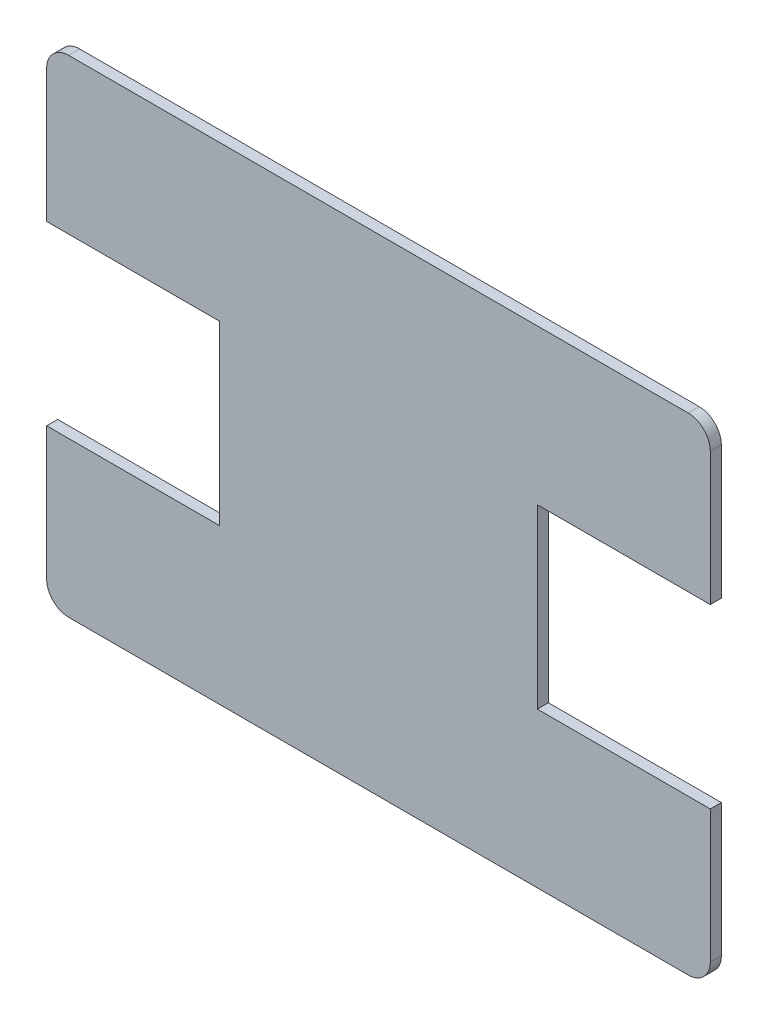
SolidWorks part; units mm, degrees
ref_plane "Front Plane" through (0, 0, 0) normal (0, 0, 1) x (1, 0, 0)
ref_plane "Top Plane" through (0, 0, 0) normal (0, 1, 0) x (1, 0, 0)
ref_plane "Right Plane" through (0, 0, 0) normal (1, 0, 0) x (0, 0, -1)
sketch "Sketch1" plane through (0, 0, 0) normal (0, 0, 1) x (1, 0, 0)
  line L0 (-150, 40) -> (-71.83, 40)
  line L1 (-140, 110) -> (140, 110)
  line L2 (-150, 100) -> (-150, 40)
  line L3 (-140, -110) -> (140, -110)
  line L4 (150, 100) -> (150, 40)
  line L5 (-71.83, 40) -> (-71.83, -40)
  line L6 (-71.83, -40) -> (-150, -40)
  line L7 (-150, 110) -> (150, -110) construction
  line L8 (0, 110) -> (0, -110) construction
  line L9 (150, 40) -> (71.83, 40)
  line L10 (71.83, 40) -> (71.83, -40)
  line L11 (71.83, -40) -> (150, -40)
  line L12 (-150, -40) -> (-150, -100)
  line L13 (150, -40) -> (150, -100)
  arc A0 (-150, -100) -> (-140, -110) centre (-140, -100) ccw
  arc A1 (140, -110) -> (150, -100) centre (140, -100) ccw
  arc A2 (140, 110) -> (150, 100) centre (140, 100) cw
  arc A3 (-140, 110) -> (-150, 100) centre (-140, 100) ccw
  point P6 (-71.83, 0)
  point P9 (0, 0)
  point P19 (-150, -110)
  point P25 (150, 110)
  dimension "D6" = 10
  dimension "D1" = 300
  dimension "D2" = 220
  dimension "D3" = 78.17
  dimension "D4" = 80
  dimension "D5" = 110
extrude "Boss-Extrude1" add sketch "Sketch1" along normal blind 5
sketch "Sketch2" plane through (0, 0, 5) normal (0, 0, 1) x (1, 0, 0)
  line L0 (-150, 40) -> (-71.83, 40) construction
  line L1 (-71.83, 40) -> (-71.83, -40) construction
  line L2 (0, 110) -> (0, -110) construction
  line L3 (140, 110) -> (-140, 110) construction
  line L4 (-140, -110) -> (140, -110) construction
  circle A0 centre (-56.13, 16) radius 2
  circle A1 centre (-37.13, 16) radius 2
  circle A2 centre (-18.13, 16) radius 2
  circle A3 centre (-56.13, -16) radius 2
  circle A4 centre (-37.13, -16) radius 2
  circle A5 centre (-18.13, -16) radius 2
  circle A6 centre (-109.03, 50.84) radius 2
  circle A7 centre (-109.03, 88.84) radius 2
  circle A8 centre (109.03, 88.84) radius 2
  circle A9 centre (109.03, 50.84) radius 2
  circle A10 centre (18.13, -16) radius 2
  circle A11 centre (37.13, -16) radius 2
  circle A12 centre (56.13, -16) radius 2
  circle A13 centre (18.13, 16) radius 2
  circle A14 centre (37.13, 16) radius 2
  circle A15 centre (56.13, 16) radius 2
  dimension "D1" = 4
  dimension "D2" = 4
  dimension "D3" = 4
  dimension "D4" = 4
  dimension "D5" = 4
  dimension "D6" = 4
  dimension "D7" = 4
  dimension "D8" = 4
  dimension "D9" = 32
  dimension "D10" = 24
  dimension "D11" = 15.7
  dimension "D12" = 19
  dimension "D13" = 19
  dimension "D14" = 19
  dimension "D15" = 34.84
  dimension "D16" = 52.9
  dimension "D17" = 38
